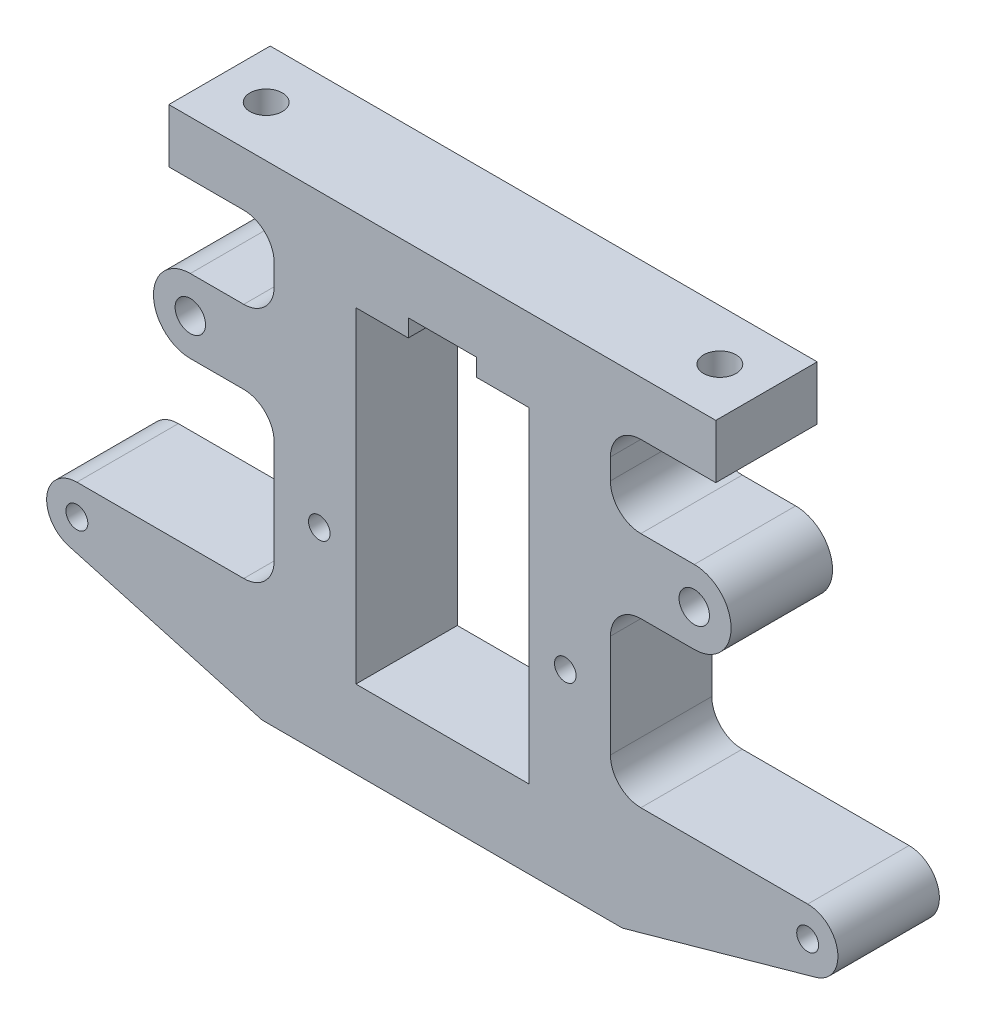
SolidWorks part; units mm, degrees
ref_plane "Front Plane" through (0, 0, 0) normal (0, 0, 1) x (1, 0, 0)
ref_plane "Top Plane" through (0, 0, 0) normal (0, 1, 0) x (1, 0, 0)
ref_plane "Right Plane" through (0, 0, 0) normal (1, 0, 0) x (0, 0, -1)
sketch "Sketch1" plane through (0, 0, 0) normal (0, 0, 1) x (1, 0, 0)
  line L0 (22.563, -49.8031) -> (46.7772, -43.0356)
  line L1 (45.7573, -35.5973) -> (24.863, -35.5973)
  line L2 (-21.053, -18.898) -> (-21.053, -31.7873)
  line L3 (31.5546, -15.088) -> (24.863, -15.088)
  line L4 (31.5546, -5.8651) -> (24.863, -5.8651)
  line L5 (0, 17.0214) -> (0, -71.4741) construction
  line L6 (34.2514, 11.1077) -> (-34.2514, 11.1077)
  line L7 (-46.9764, -35.6716) -> (-45.6486, -39.7177) construction
  line L9 (34.2514, 11.1077) -> (34.2514, 4.3512)
  line L10 (34.2514, 4.3512) -> (24.863, 4.3512)
  line L11 (-34.2514, 4.3512) -> (-24.863, 4.3512)
  line L12 (-34.2514, 11.1077) -> (-34.2514, 4.3512)
  line L13 (-21.053, 0.5412) -> (-21.053, -2.0551)
  line L14 (-45.7573, -35.5973) -> (-24.863, -35.5973)
  line L15 (-31.5546, -15.088) -> (-24.863, -15.088)
  line L16 (-31.5546, -5.8651) -> (-24.863, -5.8651)
  line L17 (-10.8167, 0.7917) -> (-10.8167, -40.0238)
  line L18 (-10.8167, -40.0238) -> (10.8378, -40.0238)
  line L19 (-10.8167, 0.7917) -> (10.8378, 0.7917)
  line L20 (10.8378, 0.7917) -> (10.8378, -40.0238)
  line L21 (46.9764, -35.6716) -> (45.6486, -39.7177) construction
  line L22 (21.053, -18.898) -> (21.053, -31.7873)
  line L23 (21.053, 0.5412) -> (21.053, -2.0551)
  line L24 (22.563, -49.8031) -> (-22.563, -49.8031)
  line L25 (-22.563, -49.8031) -> (-46.7772, -43.0356)
  circle A0 centre (45.7573, -39.3863) radius 1.3716
  arc A1 (45.7573, -35.5973) -> (46.7772, -43.0356) centre (45.7573, -39.3863) cw
  circle A2 centre (31.5546, -10.4765) radius 1.905
  arc A3 (21.053, -31.7873) -> (24.863, -35.5973) centre (24.863, -31.7873) ccw
  arc A4 (-45.7573, -35.5973) -> (-46.7772, -43.0356) centre (-45.7573, -39.3863) ccw
  circle A5 centre (-31.5546, -10.4765) radius 1.905
  arc A6 (-31.5546, -15.088) -> (-31.5546, -5.8651) centre (-31.5546, -10.4765) cw
  circle A7 centre (-45.7573, -39.3863) radius 1.3716
  arc A8 (-21.053, -31.7873) -> (-24.863, -35.5973) centre (-24.863, -31.7873) cw
  arc A9 (31.5546, -15.088) -> (31.5546, -5.8651) centre (31.5546, -10.4765) ccw
  arc A10 (-21.053, 0.5412) -> (-24.863, 4.3512) centre (-24.863, 0.5412) ccw
  arc A11 (-24.863, -5.8651) -> (-21.053, -2.0551) centre (-24.863, -2.0551) ccw
  arc A12 (24.863, -5.8651) -> (21.053, -2.0551) centre (24.863, -2.0551) cw
  arc A13 (21.053, 0.5412) -> (24.863, 4.3512) centre (24.863, 0.5412) cw
  arc A14 (21.053, -18.898) -> (24.863, -15.088) centre (24.863, -18.898) cw
  arc A15 (-21.053, -18.898) -> (-24.863, -15.088) centre (-24.863, -18.898) ccw
  point P2 (0, -34.0825)
  point P9 (0, -49.8031)
  point P10 (0, 22.6239)
  point P14 (0, 71.4741)
  point P29 (0, -40.9648)
  point P30 (0, 11.1077)
  point P37 (0, 11.1077)
  point P38 (0, 11.1077)
  point P40 (0, 11.1077)
  point P41 (0, -22.6234)
  point P43 (0, -44.4611)
  point P48 (0, 4.3512)
  point P49 (0, -34.3115)
  point P58 (0, 11.1077)
  point P68 (21.053, -15.088)
  point P71 (-21.053, -15.088)
  dimension "D1" = 3.81
  dimension "D2" = 3.81
  dimension "D3" = 3.81
  dimension "D4" = 2.7432
extrude "Extrude1" add sketch "Sketch1" along normal mid plane 12.7
sketch "Sketch2" plane through (0, 11.1077, 0) normal (0, 1, 0) x (1, 0, 0)
  line L2 (0, 29.079) -> (0, -25.417) construction
  circle A0 centre (28.4072, 0) radius 2.032
  circle A1 centre (-28.4072, 0) radius 2.032
  dimension "D2" = 4.064
extrude "Extrude2" cut sketch "Sketch2" against normal blind 12.7
sketch "Sketch3" plane through (0, 0, 6.35) normal (0, 0, 1) x (1, 0, 0)
  line L0 (-21.053, -25.3426) -> (21.053, -25.3426) construction
  line L1 (0, -25.3426) -> (0, -31.2028) construction
  line L2 (-21.053, -18.898) -> (-21.053, -31.7873) construction
  line L3 (21.053, -31.7873) -> (21.053, -18.898) construction
  circle A0 centre (-15.4026, -25.3426) radius 1.3497
  circle A1 centre (15.4026, -25.3426) radius 1.3497
extrude "Cut-Extrude1" cut sketch "Sketch3" against normal through all
sketch "Sketch4" plane through (0, 0, 6.35) normal (0, 0, 1) x (1, 0, 0)
  line L0 (10.8378, 0.7917) -> (-10.8167, 0.7917) construction
  line L1 (4.279, 2.9782) -> (-4.2579, 2.9782)
  line L2 (4.279, 2.9782) -> (4.279, -1.3947)
  line L3 (4.279, -1.3947) -> (-4.2579, -1.3947)
  line L4 (-4.2579, 2.9782) -> (-4.2579, -1.3947)
  line L5 (4.279, 2.9782) -> (-4.2579, -1.3947) construction
  line L6 (4.279, -1.3947) -> (-4.2579, 2.9782) construction
  point P0 (0.0105, 0.7917)
extrude "Cut-Extrude2" cut sketch "Sketch4" against normal through all
